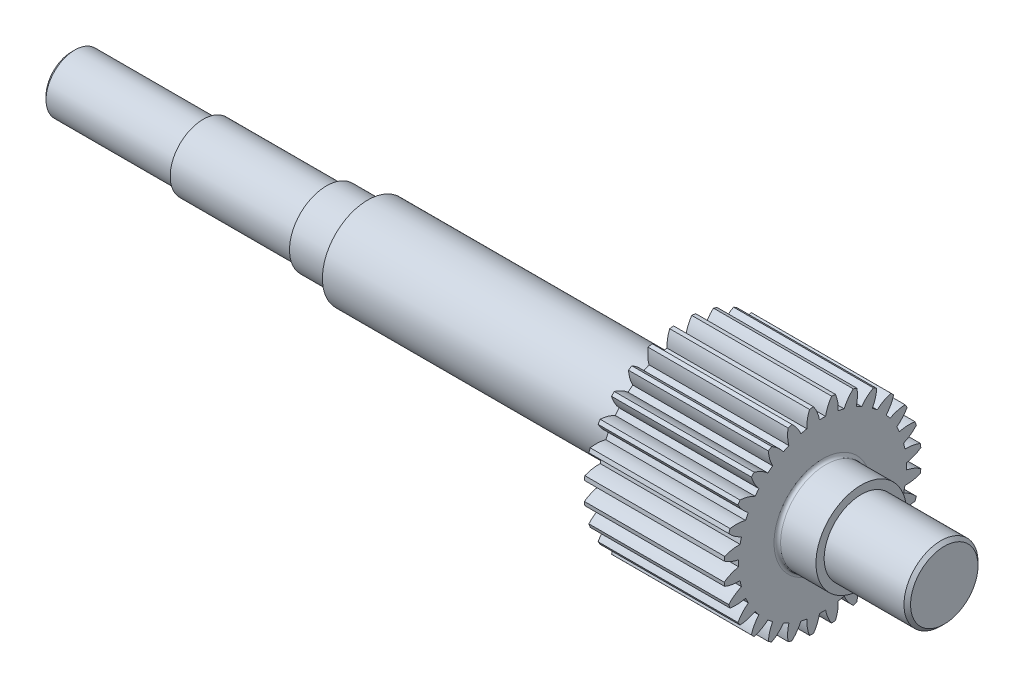
SolidWorks part; units mm, degrees
material "Plain Carbon Steel"
ref_plane "Plane1" through (0, 0, 0) normal (0, 0, 1) x (1, 0, 0)
ref_plane "Plane2" through (0, 0, 0) normal (0, 1, 0) x (1, 0, 0)
ref_plane "Plane3" through (0, 0, 0) normal (1, 0, 0) x (0, 0, -1)
sketch "HoldingSke" plane through (0, 0, 0) normal (0, 1, 0) x (1, 0, 0)
  line L0 (0, 0) -> (0.2207, -0.1174)
  line L1 (-15, 0) -> (100, 0) construction
  line L2 (0, 0) -> (-2.1039, 2.3779)
  line L3 (0, 0) -> (-11.863, 4.5341)
  line L4 (0, 0) -> (7.6251, 4.0544)
  line L5 (0, 0) -> (-46.8476, -17.4728)
  line L6 (0, 0) -> (-70.4618, -47.5408)
  line L7 (-2.1039, 2.3779) -> (16.1923, 85.3855)
  line L8 (-76.2, 54.61) -> (-76.1, 54.61)
  line L9 (-71.009, 38.7566) -> (-53.1078, 45.2721)
  line L10 (-76.2, 71.12) -> (104.1128, 71.12)
  line L11 (0, 0) -> (-85, 0)
  line L12 (-76.2, 101.6) -> (-76.073, 101.6)
  line L13 (24.9733, 27.94) -> (52.9518, 28.4284)
  line L14 (24.9733, 27.94) -> (24.9743, 27.94)
  line L15 (24.9733, 27.94) -> (100.4006, 29.5858)
  line L16 (-63.627, -4) -> (-12.827, -4)
  circle A0 centre (0, 0) radius 0.4
  circle A1 centre (0, 0) radius 37.5
  circle A2 centre (0, 0) radius 37.5
  circle A3 centre (0, 0) radius 0.4
  dimension "MHD" = 75
  dimension "Hub_dia" = 75
  dimension "Bore" = 0.8
  dimension "MBD" = 0.8
  dimension "Num_teeth" = 28
  dimension "Pitch" = 0.25
  dimension "Overall_len" = 50
  dimension "Show_teeth" = 28
  dimension "Thickness" = 85
  dimension "OAL" = 85.0001
  dimension "T_dim" = 0.1
  dimension "Ap" = 20
  dimension "H" = 19.05
  dimension "Pitch_radius" = 180.3128
  dimension "Width" = 85
  dimension "Backlash" = 0.127
  dimension "Addendum_fac" = 1
  dimension "Dedendum_fac" = 1.25
  dimension "Clearance_fac" = 0.25
  dimension "Dedendum_add" = 0.001
  dimension "Module" = 4
sketch "BasProSke" plane through (0, 0, 0) normal (0, 1, 0) x (1, 0, 0)
  line L0 (-10, 0) -> (60, 0) construction
  line L1 (0, 0) -> (0, 60)
  line L2 (0, 0) -> (85, 0)
  line L3 (85, 0) -> (85, 60)
  line L4 (85, 60) -> (0, 60)
  dimension "Thickness" = 85
  dimension "Diameter" = 120
revolve "Base-Revolve" add sketch "BasProSke" angle 360 about L0
sketch "TooCutSke" plane through (0, 0, 0) normal (1, 0, 0) x (0, 0, -1)
  line L1 (0, 0) -> (0, 107) construction
  line L2 (0, 0) -> (-3.3621, 55.899) construction
  line L3 (0, 0) -> (-12.523, 111.1446) construction
  line L4 (-3.3621, 55.899) -> (-6.2615, 55.5723) construction
  arc A0 (1.846, 50.9656) -> (-1.846, 50.9656) centre (0, 0) ccw
  arc A1 (5.5418, 59.769) -> (-5.5418, 59.769) centre (0, 0) ccw
  circle A2 centre (0, 0) radius 56 construction
  circle A3 centre (0, 0) radius 52.6228 construction
  arc A4 (-1.846, 50.9656) -> (-5.5418, 59.769) centre (-23.8732, 46.8959) ccw
  arc A5 (5.5418, 59.769) -> (1.846, 50.9656) centre (23.8732, 46.8959) ccw
  dimension "Root_dia" = 101.998
  dimension "Overcut_dia" = 120.0508
  dimension "Pitch_dia" = 112
  dimension "Base_dia" = 105.2456
  dimension "Flank_rad" = 22.4
  dimension "Half_ang" = 6.429
  dimension "Half_CT" = 2.9177
extrude "ToothCut" cut sketch "TooCutSke" along normal through all
fillet "Breaks" [suppressed] radius 0.08
fillet "RootFillets" [suppressed] radius 1.001
pattern_circular "TeethCuts" count 28 every 12.857 about axis through (-10, 0, 0) along (1, 0, 0) of "ToothCut", "RootFillets", "Breaks"
sketch "HubNeaOneSke" plane through (0, 0, 0) normal (-1, 0, 0) x (0, 0, 1)
  circle A0 centre (0, 0) radius 37.5
  dimension "Diameter" = 75
extrude "HubNearOne" [suppressed] add sketch "HubNeaOneSke" along normal blind 38.0001
sketch "HubNeaBotSke" plane through (0, 0, 0) normal (-1, 0, 0) x (0, 0, 1)
  circle A0 centre (0, 0) radius 37.5
  dimension "Diameter" = 75
extrude "HubNearBoth" [suppressed] add sketch "HubNeaBotSke" along normal blind 19
ref_plane "FarPln" through (85, 0, 0) normal (1, 0, 0) x (0, 0, -1)
sketch "HubFarSke" plane through (85, 0, 0) normal (1, 0, 0) x (0, 0, -1)
  circle A0 centre (0, 0) radius 37.5
  dimension "Diameter" = 75
extrude "HubFar" [suppressed] add sketch "HubFarSke" along normal blind 19
sketch "BorSke" plane through (0, 0, 0) normal (1, 0, 0) x (0, 0, -1)
  circle A0 centre (0, 0) radius 0.4
  dimension "Diameter" = 0.8
extrude "Bore" cut sketch "BorSke" along normal mid plane 170.0001
sketch "KeySke" plane through (0, 0, 0) normal (1, 0, 0) x (0, 0, -1)
  line L0 (-0.05, 0) -> (-0.05, 0.5)
  line L1 (-0.05, 0.5) -> (0.05, 0.5)
  line L2 (0.05, 0.5) -> (0.05, 0)
  line L3 (0, 0) -> (0, 34) construction
  line L4 (-0.05, 0) -> (0.05, 0)
  dimension "Offset" = 0.5
  dimension "Width" = 0.1
extrude "Keyway" [suppressed] cut sketch "KeySke" along normal mid plane 170.0001
pattern_circular "Keyway2" [suppressed] count 2 every 90 about axis through (-10, 0, 0) along (1, 0, 0)
sketch "Sketch1" plane through (0, 0, 0) normal (0, 1, 0) x (1, 0, 0)
  line L0 (159, 0) -> (-371.5, 0) construction
  line L1 (159, 0) -> (159, 22.5)
  line L2 (159, 22.5) -> (108.5, 22.5)
  line L3 (108.5, 22.5) -> (108.5, 27.5)
  line L4 (108.5, 27.5) -> (-191.5, 27.5)
  line L5 (-191.5, 27.5) -> (-191.5, 22.5)
  line L6 (-191.5, 22.5) -> (-216.5, 22.5)
  line L7 (-216.5, 22.5) -> (-216.5, 20)
  line L8 (-216.5, 20) -> (-291.5, 20)
  line L9 (-291.5, 20) -> (-291.5, 17.5)
  line L10 (-291.5, 17.5) -> (-371.5, 17.5)
  line L11 (-371.5, 17.5) -> (-371.5, 0)
  line L12 (85, 41.57) -> (85, 43.2658) construction
  line L13 (0, 50.1553) -> (0, 40.9975) construction
  line L14 (159, 0) -> (-371.5, 0)
  dimension "D1" = 45
  dimension "D2" = 55
  dimension "D3" = 50.5
  dimension "D4" = 23.5
  dimension "D5" = 191.5
  dimension "D6" = 25
  dimension "D7" = 75
  dimension "D8" = 80
  dimension "D9" = 45
  dimension "D10" = 40
  dimension "D11" = 35
revolve "Revolve1" add sketch "Sketch1" angle 360 about L0
fillet "Fillet1" radius 2 2 edges at (0, 0, -27.5) (85, 0, 27.5)
chamfer "Chamfer1" distance 2 angle 45 2 edges at (-371.5, 0, -17.5) (159, 0, -22.5)
ref_plane "Plane4" through (0, 0, -17.5) normal (0, 0, -1) x (-1, 0, 0)
sketch "Sketch2" plane through (0, 0, -17.5) normal (0, 0, -1) x (-1, 0, 0)
  line L0 (327.5, 0) -> (415.5, 0) construction
  line L1 (371.5, -15.5) -> (371.5, 15.5) construction
  line L2 (327.5, 6) -> (415.5, 6)
  line L3 (327.5, -6) -> (415.5, -6)
  arc A0 (327.5, 6) -> (327.5, -6) centre (327.5, 0) ccw
  arc A1 (415.5, -6) -> (415.5, 6) centre (415.5, 0) ccw
  point P5 (371.5, 0)
  dimension "D2" = 6
  dimension "D1" = 88
extrude "Cut-Extrude1" cut sketch "Sketch2" against normal blind 4.939
equation "' \"Module@HoldingSke\" = 6.35"
equation "' \"Num_teeth@HoldingSke\" = 12"
equation "' \"Ap@HoldingSke\" =  20"
equation "' \"Ap@HoldingSke\" = 20"
equation "' \"Width@HoldingSke\" = 0.5 * 25.4"
equation "' \"Hub_dia@HoldingSke\"= 1 * 25.4"
equation "' \"Hub_dia@HoldingSke\" = 1 * 25.4"
equation "' \"Overall_len@HoldingSke\" = 1.0 * 25.4"
equation "' \"Bore@HoldingSke\" = 0.75 * 25.4"
equation "' \"T_dim@HoldingSke\" = 0.1 * 25.4"
equation "' \"Width@KeySke\" = 0.25 * 25.4"
equation "' \"Show_teeth@HoldingSke\" = 13"
equation "' \"Backlash@HoldingSke\" = 0.009 * 25.4"
equation "' \"Addendum_fac@HoldingSke\" = 1.0"
equation "' \"Dedendum_fac@HoldingSke\" = 1.25"
equation "' \"Dedendum_add@HoldingSke\" = 0.00005 * 25.4"
equation "' \"Clearance_fac@HoldingSke\" = 0.25"
equation "\"Pitch@HoldingSke\" = 1 / \"Module@HoldingSke\""
equation "\"Overcut_dia@TooCutSke\" = (\"Num_teeth@HoldingSke\" + 2 * \"Addendum_fac@HoldingSke\") / \"Pitch@HoldingSke\" + 0.002 * 25.4"
equation "\"Pitch_dia@TooCutSke\" = \"Num_teeth@HoldingSke\" / \"Pitch@HoldingSke\""
equation "\"Base_dia@TooCutSke\" = \"Num_teeth@HoldingSke\" / \"Pitch@HoldingSke\" * cos((\"Ap@HoldingSke\"  * 3.14159265 / 180))"
equation "\"Root_dia@TooCutSke\" = (\"Num_teeth@HoldingSke\" + 2) / \"Pitch@HoldingSke\" - 2 * (\"Addendum_fac@HoldingSke\" + \"Dedendum_fac@HoldingSke\") / \"Pitch@HoldingSke\" - \"Dedendum_add@HoldingSke\" * 2"
equation "\"Half_ang@TooCutSke\" = 180 / \"Num_teeth@HoldingSke\""
equation "\"Half_CT@TooCutSke\" = \"Num_teeth@HoldingSke\" / \"Pitch@HoldingSke\" * sin((3.14159265 / 2 / \"Num_teeth@HoldingSke\")) / 2 - 7 * \"Backlash@HoldingSke\" / 4"
equation "\"Flank_rad@TooCutSke\" = \"Num_teeth@HoldingSke\" / \"Pitch@HoldingSke\" / 5"
equation "\"Radius@RootFillets\" = \"Clearance_fac@HoldingSke\" / \"Pitch@HoldingSke\" + \"Dedendum_add@HoldingSke\""
equation "\"Break_rad@Breaks\" = 0.02 / \"Pitch@HoldingSke\""
equation "\"Thickness@HoldingSke\" = \"Width@HoldingSke\""
equation "\"OAL@HoldingSke\" = \"Thickness@HoldingSke\""
equation "\"MHD@HoldingSke\" = (\"Num_teeth@HoldingSke\" + 2) / \"Pitch@HoldingSke\" - 2 * (\"Addendum_fac@HoldingSke\" + \"Dedendum_fac@HoldingSke\")  / \"Pitch@HoldingSke\" - \"Dedendum_add@HoldingSke\" * 2"
equation "\"MBD@HoldingSke\" = (\"Num_teeth@HoldingSke\" + 2) / \"Pitch@HoldingSke\" - 2 * (\"Addendum_fac@HoldingSke\" + \"Dedendum_fac@HoldingSke\")  / \"Pitch@HoldingSke\" - \"Dedendum_add@HoldingSke\" * 2 - 0.002 * 25.4"
equation "\"MHD@HoldingSke\" = ((sgn( \"MHD@HoldingSke\" - \"Hub_dia@HoldingSke\" )-1)*( \"MHD@HoldingSke\" - \"Hub_dia@HoldingSke\" ))/-2+ \"Hub_dia@HoldingSke\""
equation "\"MBD@HoldingSke\" = ((sgn( \"MBD@HoldingSke\" - \"Bore@HoldingSke\" )-1)*( \"MBD@HoldingSke\" - \"Bore@HoldingSke\" ))/-2+ \"Bore@HoldingSke\""
equation "\"OAL@HoldingSke\" = ((sgn( \"OAL@HoldingSke\" - \"Overall_len@HoldingSke\" )+1)*( \"OAL@HoldingSke\" - \"Overall_len@HoldingSke\" ))/2 + \"Overall_len@HoldingSke\" + 0.000002 * 25.4"
equation "\"Num_teeth@TeethCuts\" = int( \"Show_teeth@HoldingSke\" ) + 1"
equation "\"Num_teeth@TeethCuts\" = ((sgn( \"Num_teeth@TeethCuts\" - \"Num_teeth@HoldingSke\" )-1)*( \"Num_teeth@TeethCuts\" - \"Num_teeth@HoldingSke\" ))/-2+ \"Num_teeth@HoldingSke\""
equation "\"Num_teeth@TeethCuts\" = ((sgn( \"Num_teeth@TeethCuts\" - 2.0)+1)*( \"Num_teeth@TeethCuts\" - 2.0))/2 +2.0"
equation "\"Angle@TeethCuts\" = 360.0 / \"Num_teeth@HoldingSke\""
equation "\"Diameter@BasProSke\" = (\"Num_teeth@HoldingSke\" + 2 * \"Addendum_fac@HoldingSke\") / \"Pitch@HoldingSke\""
equation "\"Thickness@BasProSke\"  = \"Thickness@HoldingSke\""
equation "' \"Fillet_rad@BasProSke\" =  \"Thickness@HoldingSke\" * 0.05"
equation "' \"Fillet_rad@BasProSke\" = \"Thickness@HoldingSke\" * 0.05"
equation "\"MHD@HoldingSke\" = ((sgn( \"MHD@HoldingSke\" - \"Root_dia@TooCutSke\" )-1)*( \"MHD@HoldingSke\" - \"Root_dia@TooCutSke\" ))/-2+ \"Root_dia@TooCutSke\""
equation "\"Diameter@HubNeaOneSke\" = \"MHD@HoldingSke\""
equation "\"Length@HubNearOne\" = \"OAL@HoldingSke\" - \"Thickness@BasProSke\""
equation "\"Diameter@HubNeaBotSke\" = \"MHD@HoldingSke\""
equation "\"Length@HubNearBoth\" = ( \"OAL@HoldingSke\" - \"Thickness@BasProSke\" ) / 2.0"
equation "\"Thickness@FarPln\" = \"Thickness@BasProSke\""
equation "\"Diameter@HubFarSke\" = \"MHD@HoldingSke\""
equation "\"Length@HubFar\" = ( \"OAL@HoldingSke\" - \"Thickness@BasProSke\" ) / 2.0"
equation "\"Diameter@BorSke\" = \"MBD@HoldingSke\""
equation "\"D1@Bore\" = \"OAL@HoldingSke\" * 2.0"
equation "\"D1@Keyway\" = \"OAL@HoldingSke\" * 2.0"
equation "\"Offset@KeySke\" = \"T_dim@HoldingSke\" + \"MBD@HoldingSke\" / 2.0"
